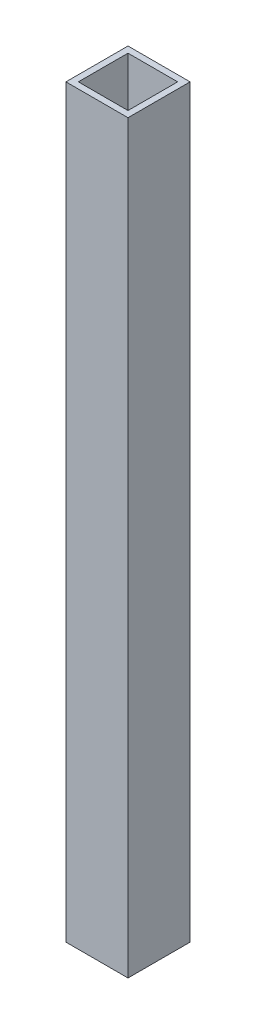
SolidWorks part; units mm, degrees
material "氧化铝"
ref_plane "前视基准面" through (0, 0, 0) normal (0, 0, 1) x (1, 0, 0)
ref_plane "上视基准面" through (0, 0, 0) normal (0, 1, 0) x (1, 0, 0)
ref_plane "右视基准面" through (0, 0, 0) normal (1, 0, 0) x (0, 0, -1)
other "Configuration Table"
sketch "草图1" plane through (0, 0, 0) normal (0, 1, 0) x (1, 0, 0)
  line L1 (-4, 4) -> (4, 4)
  line L2 (-4, 4) -> (-4, -4)
  line L3 (-4, -4) -> (4, -4)
  line L4 (4, 4) -> (4, -4)
  line L5 (-4, 4) -> (4, -4) construction
  line L6 (-4, -4) -> (4, 4) construction
  line L7 (-5, 5) -> (5, 5)
  line L8 (-5, 5) -> (-5, -5)
  line L9 (-5, -5) -> (5, -5)
  line L10 (5, 5) -> (5, -5)
  line L11 (-5, 5) -> (5, -5) construction
  line L12 (-5, -5) -> (5, 5) construction
  point P0 (0, 0)
  point P6 (0, 0)
  dimension "D1" = 1
  dimension "D2" = 1
  dimension "D3" = 10
  dimension "D4" = 10
extrude "凸台-拉伸1" add sketch "草图1" along normal blind 120
